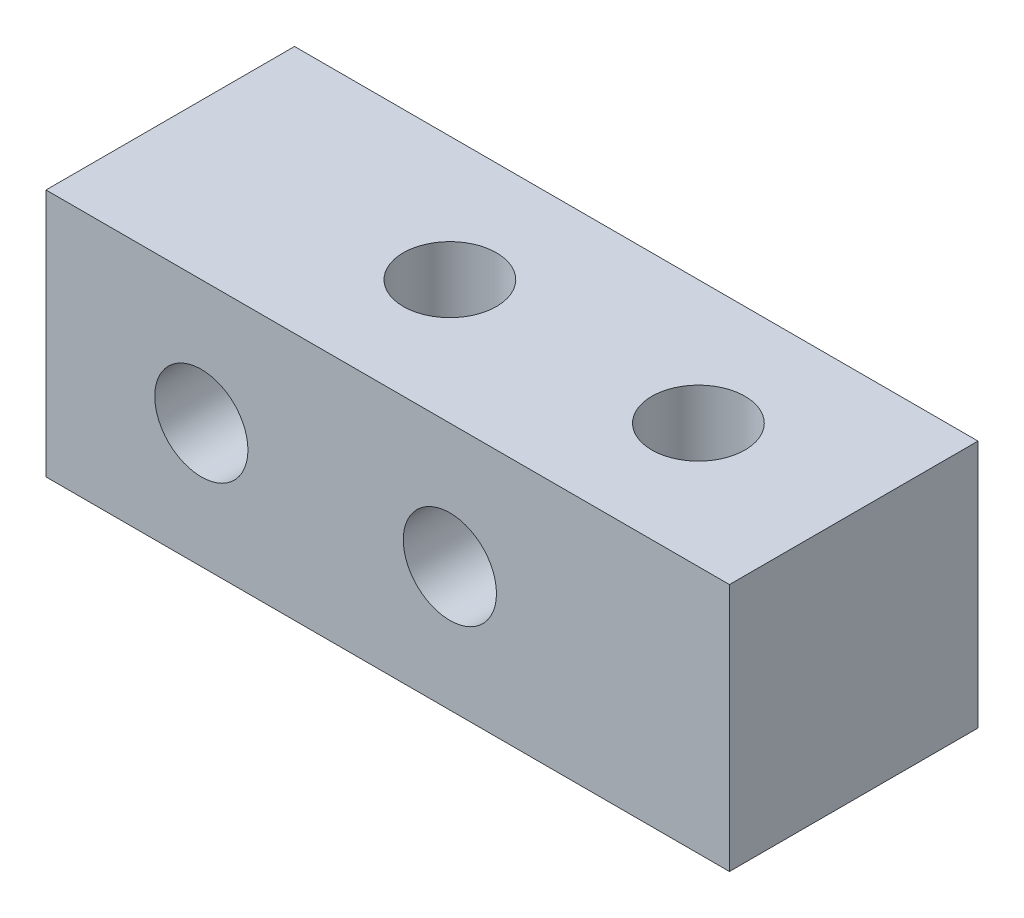
SolidWorks part; units mm, degrees
material "1060 合金"
ref_plane "前视基准面" through (0, 0, 0) normal (0, 0, 1) x (1, 0, 0)
ref_plane "上视基准面" through (0, 0, 0) normal (0, 1, 0) x (1, 0, 0)
ref_plane "右视基准面" through (0, 0, 0) normal (1, 0, 0) x (0, 0, -1)
other "Configuration Table"
sketch "草图1" plane through (0, 0, 0) normal (0, 1, 0) x (1, 0, 0)
  line L1 (-11, -4) -> (11, -4)
  line L2 (-11, -4) -> (-11, 4)
  line L3 (-11, 4) -> (11, 4)
  line L4 (11, -4) -> (11, 4)
  line L5 (-11, -4) -> (11, 4) construction
  line L6 (-11, 4) -> (11, -4) construction
  circle A0 centre (6, 0) radius 1.5
  circle A1 centre (-2, 0) radius 1.5
  point P0 (0, 0)
  dimension "D3" = 3
  dimension "D6" = 3
  dimension "D7" = 8
  dimension "D1" = 22
  dimension "D2" = 8
  dimension "D4" = 5
  dimension "D5" = 4
  dimension "D8" = 4
extrude "凸台-拉伸1" add sketch "草图1" along normal blind 8
sketch "草图2" plane through (0, 0, 4) normal (0, 0, 1) x (1, 0, 0)
  line L0 (-11, 4) -> (14.9105, 4) construction
  line L1 (-11, 8) -> (-11, 0) construction
  circle A0 centre (-6, 4) radius 1.5
  circle A1 centre (2, 4) radius 1.5
  dimension "D1" = 3
  dimension "D3" = 8
  dimension "D4" = 3
  dimension "D2" = 5
extrude "切除-拉伸1" cut sketch "草图2" against normal blind 8
